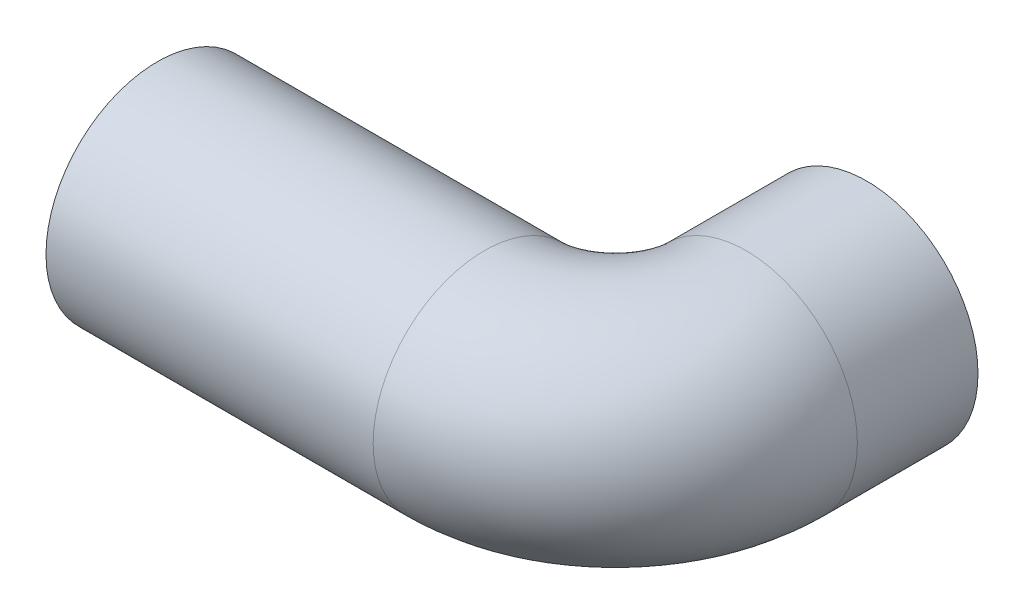
SolidWorks part; units mm, degrees
ref_plane "Front Plane" through (0, 0, 0) normal (0, 0, 1) x (1, 0, 0)
ref_plane "Top Plane" through (0, 0, 0) normal (0, 1, 0) x (1, 0, 0)
ref_plane "Right Plane" through (0, 0, 0) normal (1, 0, 0) x (0, 0, -1)
sketch3d "3DSketch1"
  line L0 (0, 0, 0) -> (0, 0, 36.87)
  line L1 (-40, 0, 76.87) -> (-140, 0, 76.87)
  arc A0 (0, 0, 36.87) -> (-40, 0, 76.87) centre (-40, 0, 36.87) ccw
  point P6 (0, 0, 76.87)
  point P7 (-40, -40, 36.87)
  dimension "D3" = 40
  dimension "D1" = 76.87
  dimension "D2" = 140
sweep "Sweep1" add path "3DSketch1" circular profile diameter 68 parameters "D3"=68
shell "Shell1" thickness 0.5
